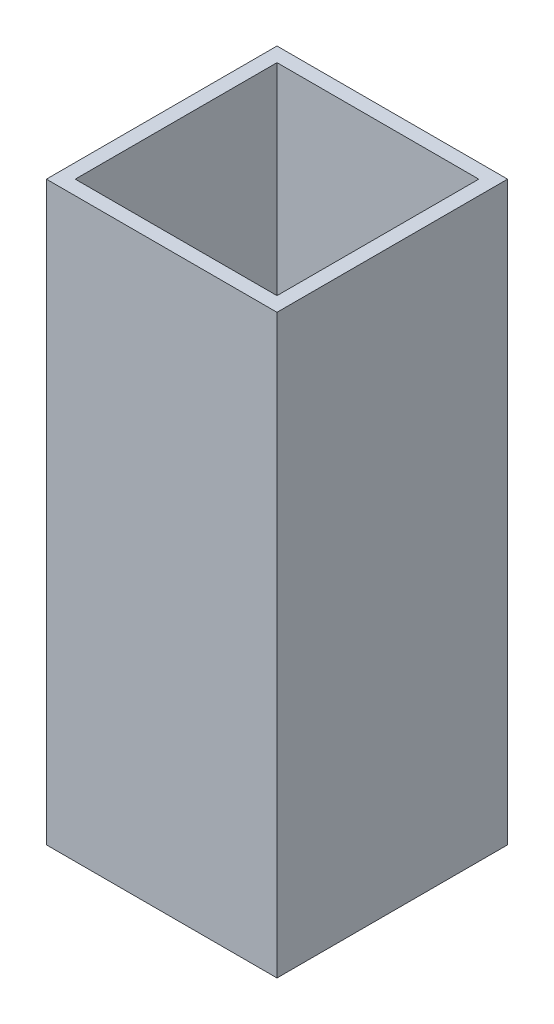
SolidWorks part; units mm, degrees
material "6061 Alloy"
ref_plane "Front Plane" through (0, 0, 0) normal (0, 0, 1) x (1, 0, 0)
ref_plane "Top Plane" through (0, 0, 0) normal (0, 1, 0) x (1, 0, 0)
ref_plane "Right Plane" through (0, 0, 0) normal (1, 0, 0) x (0, 0, -1)
sketch "Sketch1" plane through (0, 0, 0) normal (0, 1, 0) x (1, 0, 0)
  line L1 (12.7, 12.7) -> (-12.7, 12.7)
  line L2 (12.7, 12.7) -> (12.7, -12.7)
  line L3 (12.7, -12.7) -> (-12.7, -12.7)
  line L4 (-12.7, 12.7) -> (-12.7, -12.7)
  line L5 (12.7, 12.7) -> (-12.7, -12.7) construction
  line L6 (12.7, -12.7) -> (-12.7, 12.7) construction
  line L7 (11.1125, 11.1125) -> (-11.1125, 11.1125)
  line L8 (11.1125, 11.1125) -> (11.1125, -11.1125)
  line L9 (11.1125, -11.1125) -> (-11.1125, -11.1125)
  line L10 (-11.1125, 11.1125) -> (-11.1125, -11.1125)
  line L11 (11.1125, 11.1125) -> (-11.1125, -11.1125) construction
  line L12 (11.1125, -11.1125) -> (-11.1125, 11.1125) construction
  point P1 (0, 0)
  point P6 (0, 0)
  dimension "D1" = 25.4
  dimension "D2" = 25.4
  dimension "D3" = 1.5875
  dimension "D4" = 1.5875
extrude "Boss-Extrude1" add sketch "Sketch1" along normal blind 63.5
